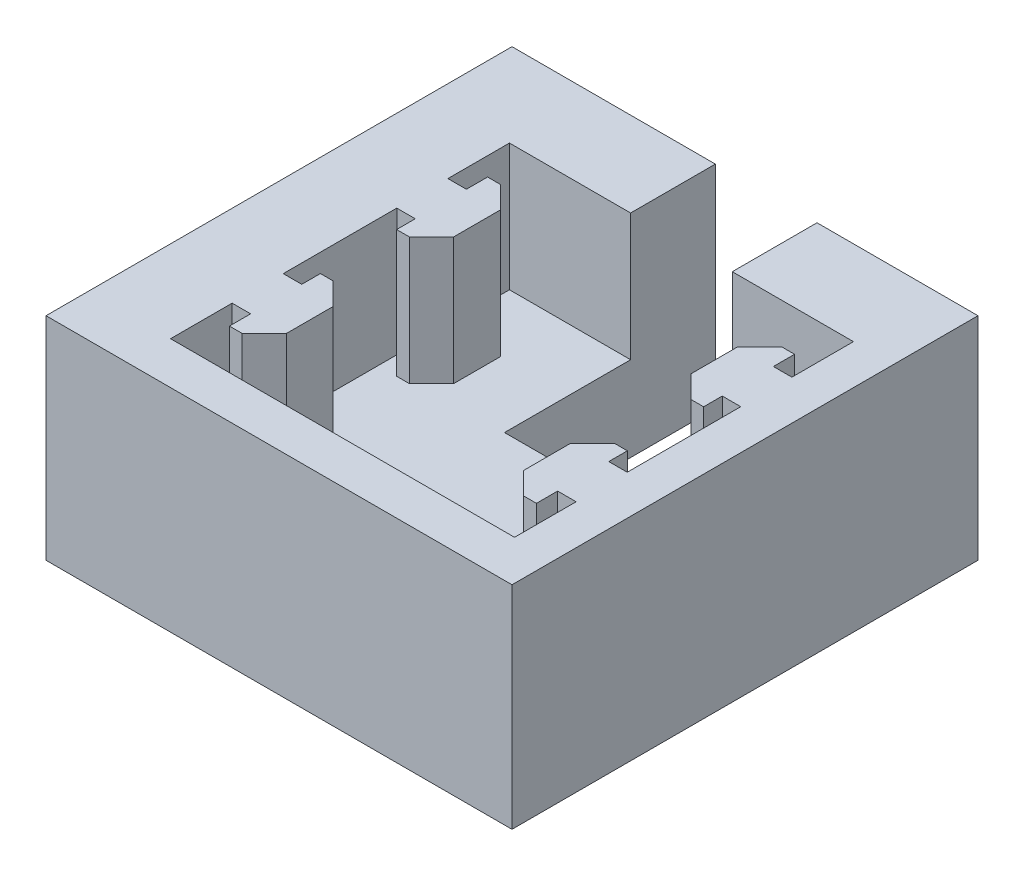
SolidWorks part; units mm, degrees
ref_plane "Front Plane" through (0, 0, 0) normal (0, 0, 1) x (1, 0, 0)
ref_plane "Top Plane" through (0, 0, 0) normal (0, 1, 0) x (1, 0, 0)
ref_plane "Right Plane" through (0, 0, 0) normal (1, 0, 0) x (0, 0, -1)
sketch "Sketch1" plane through (0, 0, 0) normal (0, 1, 0) x (1, 0, 0)
  line L1 (0, 0) -> (-55, 0)
  line L2 (0, 0) -> (0, -55)
  line L3 (0, -55) -> (-55, -55)
  line L4 (-55, 0) -> (-55, -55)
  dimension "D1" = 55
  dimension "D2" = 55
extrude "Boss-Extrude1" add sketch "Sketch1" along normal blind 10
sketch "Sketch2" plane through (0, 10, 0) normal (0, 1, 0) x (1, 0, 0)
  line L0 (-45.3163, -17.2674) -> (-43.1163, -17.2674)
  line L2 (-43.1163, -17.2674) -> (-43.1163, -14.7674)
  line L3 (-43.1163, -14.7674) -> (-41.6163, -14.7674)
  line L4 (-41.6163, -14.7674) -> (-39, -17.3837)
  line L5 (-39, -17.3837) -> (-39, -22.8837)
  line L6 (-39, -22.8837) -> (-41.6163, -25.5)
  line L7 (-41.6163, -25.5) -> (-43.1163, -25.5)
  line L8 (-43.1163, -25.5) -> (-43.1163, -23.3)
  line L9 (-43.1163, -23.3) -> (-45.3163, -23.3)
  line L10 (-45.3163, -23.3) -> (-45.3163, -17.2674)
  line L13 (-25, 0) -> (-25, -55) construction
  line L15 (-55, -30) -> (-3.9273, -30) construction
  line L18 (-6.8837, -23.3) -> (-4.6837, -23.3)
  line L19 (-6.8837, -25.5) -> (-6.8837, -23.3)
  line L20 (-8.3837, -25.5) -> (-6.8837, -25.5)
  line L21 (-11, -22.8837) -> (-8.3837, -25.5)
  line L22 (-11, -17.3837) -> (-11, -22.8837)
  line L23 (-8.3837, -14.7674) -> (-11, -17.3837)
  line L24 (-6.8837, -14.7674) -> (-8.3837, -14.7674)
  line L25 (-6.8837, -17.2674) -> (-6.8837, -14.7674)
  line L26 (-4.6837, -17.2674) -> (-6.8837, -17.2674)
  line L27 (-4.6837, -23.3) -> (-4.6837, -17.2674)
  line L28 (-43.1163, -36.7) -> (-45.3163, -36.7)
  line L29 (-43.1163, -34.5) -> (-43.1163, -36.7)
  line L30 (-41.6163, -34.5) -> (-43.1163, -34.5)
  line L31 (-39, -37.1163) -> (-41.6163, -34.5)
  line L32 (-39, -42.6163) -> (-39, -37.1163)
  line L33 (-41.6163, -45.2326) -> (-39, -42.6163)
  line L34 (-43.1163, -45.2326) -> (-41.6163, -45.2326)
  line L35 (-43.1163, -42.7326) -> (-43.1163, -45.2326)
  line L36 (-45.3163, -42.7326) -> (-43.1163, -42.7326)
  line L37 (-45.3163, -36.7) -> (-45.3163, -42.7326)
  line L38 (-6.8837, -34.5) -> (-6.8837, -36.7)
  line L39 (-8.3837, -34.5) -> (-6.8837, -34.5)
  line L40 (-11, -37.1163) -> (-8.3837, -34.5)
  line L41 (-11, -42.6163) -> (-11, -37.1163)
  line L42 (-8.3837, -45.2326) -> (-11, -42.6163)
  line L43 (-6.8837, -45.2326) -> (-8.3837, -45.2326)
  line L44 (-6.8837, -42.7326) -> (-6.8837, -45.2326)
  line L45 (-4.6837, -42.7326) -> (-6.8837, -42.7326)
  line L46 (-4.6837, -36.7) -> (-4.6837, -42.7326)
  line L47 (-6.8837, -36.7) -> (-4.6837, -36.7)
  line L48 (-55, -55) -> (0, -55) construction
  line L49 (-55, 0) -> (-55, -55) construction
  point P20 (-55, -27.5)
  point P52 (-27.5, -55)
  dimension "D1" = 2.2
  dimension "D2" = 2.2
  dimension "D3" = 2.5
  dimension "D4" = 2.2
  dimension "D5" = 3.7
  dimension "D6" = 3.7
  dimension "D7" = 5.5
  dimension "D8" = 1.5
  dimension "D9" = 1.5
  dimension "D10" = 4.5
  dimension "D11" = 14
  dimension "D12" = 0
  dimension "D13" = 2.5
  dimension "D14" = 2.5
  dimension "D15" = 0
extrude "Boss-Extrude3" add sketch "Sketch2" along normal blind 15
sketch "Sketch3" plane through (0, 10, 0) normal (0, 1, 0) x (1, 0, 0)
  line L0 (0, -55) -> (0, 0) construction
  line L1 (-55, 0) -> (0, 0)
  line L2 (-55, 0) -> (-55, -10)
  line L3 (-55, -10) -> (0, -10)
  line L4 (0, 0) -> (0, -10)
  line L6 (-55, -55) -> (0, -55)
  line L7 (-55, -55) -> (-55, -50)
  line L8 (-55, -50) -> (0, -50)
  line L9 (0, -55) -> (0, -50)
  line L10 (-55, -10) -> (-45.3, -10)
  line L11 (-55, -10) -> (-55, -50)
  line L12 (-55, -50) -> (-45.3, -50)
  line L13 (-45.3, -10) -> (-45.3, -50)
  line L14 (0, -10) -> (-4.7, -10)
  line L15 (0, -10) -> (0, -50)
  line L16 (0, -50) -> (-4.7, -50)
  line L17 (-4.7, -10) -> (-4.7, -50)
  line M15 (-45.3163, -42.7326) -> (-45.3163, -36.7)
  line M17 (-45.3163, -23.3) -> (-45.3163, -17.2674)
  line M27 (0, -55) -> (0, 0)
  line M28 (0, 0) -> (-55, 0)
  line M29 (-55, 0) -> (-55, -55)
  line M30 (-55, -55) -> (0, -55)
  line M39 (-4.6837, -17.2674) -> (-4.6837, -23.3)
  line M44 (-4.6837, -36.7) -> (-4.6837, -42.7326)
  dimension "D1" = 10
  dimension "D2" = 5
  dimension "D3" = 9.7
  dimension "D4" = 4.7
extrude "Boss-Extrude5" add sketch "Sketch3" along normal blind 15 contours L3 M29 M27 M28 | L13 L3 L8 M29 M15 M17 | L8 M29 M30 M27 | L3 L17 L8 M39 M44 M27
sketch "Sketch7" plane through (0, 25, 0) normal (0, 1, 0) x (1, 0, 0)
  line L0 (-25, 0) -> (-25, -53.168) construction
  line L1 (-31, 0) -> (-19, 0)
  line L2 (-31, 0) -> (-31, -24.8837)
  line L3 (-31, -24.8837) -> (-19, -24.8837)
  line L4 (-19, 0) -> (-19, -24.8837)
  line L8 (0, 0) -> (-55, 0) construction
  point P8 (-27.5, 0)
  dimension "D1" = 12
  dimension "D2" = 6
  dimension "D3" = 0
  dimension "D4" = 2
  dimension "D5" = 2.5
  dimension "D6" = 0
extrude "Cut-Extrude3" cut sketch "Sketch7" against normal blind 30
sketch "Sketch8" plane through (0, 0, 0) normal (0, 0, -1) x (-1, 0, 0)
  line L0 (31, 0) -> (55, 0) construction
  line L1 (55, 25) -> (55, 0) construction
  circle A0 centre (50, 9) radius 2
  dimension "D1" = 4
  dimension "D2" = 9
  dimension "D3" = 5
extrude "Cut-Extrude4" cut sketch "Sketch8" against normal blind 7
sketch "Sketch9" plane through (0, 0, 0) normal (0, -1, 0) x (1, 0, 0)
  circle A0 centre (-40, 42) radius 2
  circle A1 centre (-50, 42) radius 2
  circle A2 centre (-40, 42) radius 2 construction
  circle A3 centre (-50, 42) radius 2 construction
  dimension "D1" = 4
  dimension "D2" = 4
  dimension "D3" = 0
  dimension "D4" = 0
  dimension "D5" = 0
  dimension "D6" = 0
extrude "Cut-Extrude5" cut sketch "Sketch9" against normal blind 7
